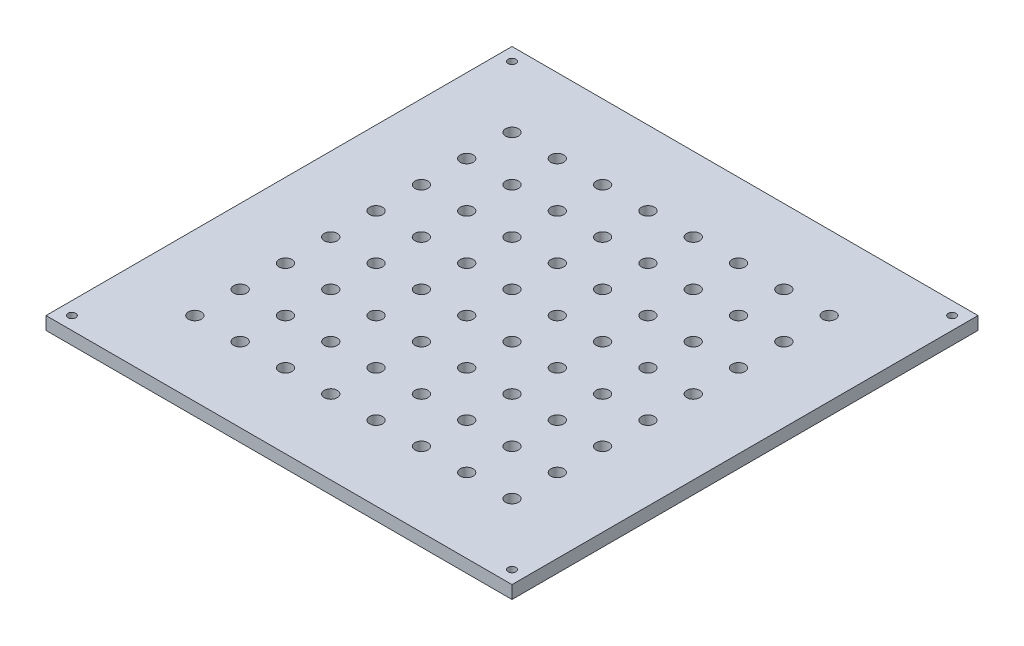
SolidWorks part; units mm, degrees
ref_plane "Front Plane" through (0, 0, 0) normal (0, 0, 1) x (1, 0, 0)
ref_plane "Top Plane" through (0, 0, 0) normal (0, 1, 0) x (1, 0, 0)
ref_plane "Right Plane" through (0, 0, 0) normal (1, 0, 0) x (0, 0, -1)
sketch "Sketch2" plane through (0, 0, 0) normal (0, 1, 0) x (1, 0, 0)
  line L1 (-90, 90) -> (90, 90)
  line L2 (-90, 90) -> (-90, -90)
  line L3 (-90, -90) -> (90, -90)
  line L4 (90, 90) -> (90, -90)
  line L5 (-90, 90) -> (90, -90) construction
  line L6 (-90, -90) -> (90, 90) construction
  line L7 (-61.25, 61.25) -> (61.25, 61.25) construction
  line L8 (-61.25, 61.25) -> (-61.25, -61.25) construction
  line L9 (-61.25, -61.25) -> (61.25, -61.25) construction
  line L10 (61.25, 61.25) -> (61.25, -61.25) construction
  line L11 (-61.25, 61.25) -> (61.25, -61.25) construction
  line L12 (-61.25, -61.25) -> (61.25, 61.25) construction
  circle A0 centre (-61.25, 61.25) radius 2.5
  circle A1 centre (-43.75, 61.25) radius 2.5
  circle A2 centre (-26.25, 61.25) radius 2.5
  circle A3 centre (-8.75, 61.25) radius 2.5
  circle A4 centre (8.75, 61.25) radius 2.5
  circle A5 centre (26.25, 61.25) radius 2.5
  circle A6 centre (43.75, 61.25) radius 2.5
  circle A7 centre (61.25, 61.25) radius 2.5
  circle A8 centre (-43.75, 43.75) radius 2.5
  circle A9 centre (-61.25, 43.75) radius 2.5
  circle A10 centre (-26.25, 43.75) radius 2.5
  circle A11 centre (-8.75, 43.75) radius 2.5
  circle A12 centre (8.75, 43.75) radius 2.5
  circle A13 centre (26.25, 43.75) radius 2.5
  circle A14 centre (43.75, 43.75) radius 2.5
  circle A15 centre (61.25, 43.75) radius 2.5
  circle A16 centre (-43.75, 26.25) radius 2.5
  circle A17 centre (-61.25, 26.25) radius 2.5
  circle A18 centre (-26.25, 26.25) radius 2.5
  circle A19 centre (-8.75, 26.25) radius 2.5
  circle A20 centre (8.75, 26.25) radius 2.5
  circle A21 centre (26.25, 26.25) radius 2.5
  circle A22 centre (43.75, 26.25) radius 2.5
  circle A23 centre (61.25, 26.25) radius 2.5
  circle A24 centre (-43.75, 8.75) radius 2.5
  circle A25 centre (-61.25, 8.75) radius 2.5
  circle A26 centre (-26.25, 8.75) radius 2.5
  circle A27 centre (-8.75, 8.75) radius 2.5
  circle A28 centre (8.75, 8.75) radius 2.5
  circle A29 centre (26.25, 8.75) radius 2.5
  circle A30 centre (43.75, 8.75) radius 2.5
  circle A31 centre (61.25, 8.75) radius 2.5
  circle A32 centre (-43.75, -8.75) radius 2.5
  circle A33 centre (-61.25, -8.75) radius 2.5
  circle A34 centre (-26.25, -8.75) radius 2.5
  circle A35 centre (-8.75, -8.75) radius 2.5
  circle A36 centre (8.75, -8.75) radius 2.5
  circle A37 centre (26.25, -8.75) radius 2.5
  circle A38 centre (43.75, -8.75) radius 2.5
  circle A39 centre (61.25, -8.75) radius 2.5
  circle A40 centre (-43.75, -26.25) radius 2.5
  circle A41 centre (-61.25, -26.25) radius 2.5
  circle A42 centre (-26.25, -26.25) radius 2.5
  circle A43 centre (-8.75, -26.25) radius 2.5
  circle A44 centre (8.75, -26.25) radius 2.5
  circle A45 centre (26.25, -26.25) radius 2.5
  circle A46 centre (43.75, -26.25) radius 2.5
  circle A47 centre (61.25, -26.25) radius 2.5
  circle A48 centre (-43.75, -43.75) radius 2.5
  circle A49 centre (-61.25, -43.75) radius 2.5
  circle A50 centre (-26.25, -43.75) radius 2.5
  circle A51 centre (-8.75, -43.75) radius 2.5
  circle A52 centre (8.75, -43.75) radius 2.5
  circle A53 centre (26.25, -43.75) radius 2.5
  circle A54 centre (43.75, -43.75) radius 2.5
  circle A55 centre (61.25, -43.75) radius 2.5
  circle A56 centre (-43.75, -61.25) radius 2.5
  circle A57 centre (-61.25, -61.25) radius 2.5
  circle A58 centre (-26.25, -61.25) radius 2.5
  circle A59 centre (-8.75, -61.25) radius 2.5
  circle A60 centre (8.75, -61.25) radius 2.5
  circle A61 centre (26.25, -61.25) radius 2.5
  circle A62 centre (43.75, -61.25) radius 2.5
  circle A63 centre (61.25, -61.25) radius 2.5
  circle A64 centre (-85, 85) radius 1.5
  circle A65 centre (85, 85) radius 1.5
  circle A66 centre (85, -85) radius 1.5
  circle A67 centre (-85, -85) radius 1.5
  point P0 (0, 0)
  point P5 (0, 0)
  dimension "D5" = 5
  dimension "D8" = 3
  dimension "D1" = 180
  dimension "D2" = 180
  dimension "D3" = 122.5
  dimension "D4" = 122.5
  dimension "D9" = 5
  dimension "D10" = 4
  dimension "D6" = 8
  dimension "D7" = 8
extrude "khung_mica" add sketch "Sketch2" along normal blind 5
